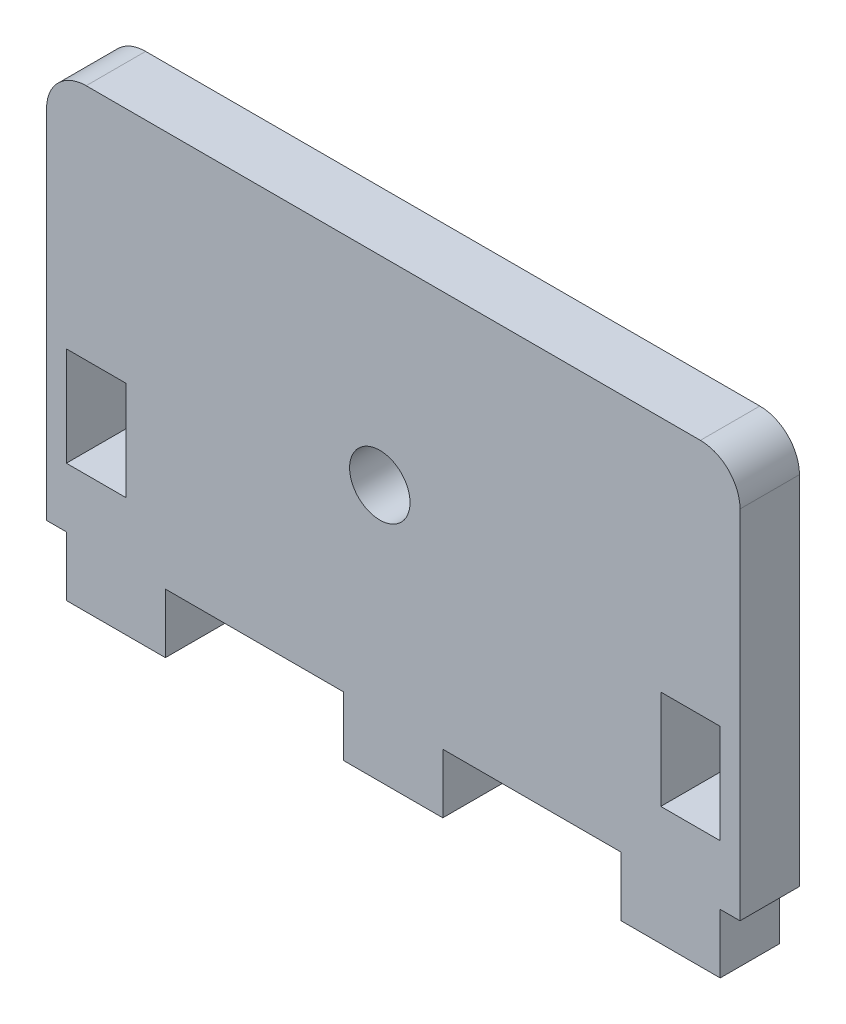
SolidWorks part; units mm, degrees
ref_plane "Front Plane" through (0, 0, 0) normal (0, 0, 1) x (1, 0, 0)
ref_plane "Top Plane" through (0, 0, 0) normal (0, 1, 0) x (1, 0, 0)
ref_plane "Right Plane" through (0, 0, 0) normal (1, 0, 0) x (0, 0, -1)
sketch "Sketch1" plane through (0, 0, 0) normal (0, 0, 1) x (1, 0, 0)
  line L0 (-11.5, -10) -> (-2.5, -10)
  line L1 (-17.5, 10) -> (17.5, 10)
  line L2 (-17.5, 10) -> (-17.5, -10)
  line L3 (-17.5, -10) -> (-16.5, -10)
  line L4 (17.5, 10) -> (17.5, -10)
  line L5 (-17.5, 10) -> (17.5, -10) construction
  line L6 (-17.5, -10) -> (17.5, 10) construction
  line L8 (-16.5, -10) -> (-16.5, -13)
  line L9 (-16.5, -13) -> (-11.5, -13)
  line L10 (-11.5, -10) -> (-11.5, -13)
  line L12 (-2.5, -10) -> (-2.5, -13)
  line L13 (-2.5, -13) -> (2.5, -13)
  line L14 (2.5, -10) -> (2.5, -13)
  line L16 (11.5, -10) -> (11.5, -13)
  line L17 (11.5, -13) -> (16.5, -13)
  line L18 (16.5, -10) -> (16.5, -13)
  line L19 (2.5, -10) -> (11.5, -10)
  line L20 (16.5, -10) -> (17.5, -10)
  point P0 (0, 0)
  point P18 (0, -13)
  dimension "D1" = 5
  dimension "D2" = 3
  dimension "D3" = 1
  dimension "D4" = 1
  dimension "D5" = 35
  dimension "D6" = 20
extrude "Boss-Extrude1" add sketch "Sketch1" along normal blind 3
fillet "Fillet1" radius 2 2 edges at (-17.5, 10, 1.5) (17.5, 10, 1.5)
sketch "Sketch4" plane through (0, 0, 3) normal (0, 0, 1) x (1, 0, 0)
  line L0 (-16.5, -13) -> (-11.5, -13) construction
  line L1 (17.5, -10) -> (17.5, 8) construction
  line L2 (-17.5, 8) -> (-17.5, -10) construction
  line L3 (-16.5, -2) -> (-13.5, -2)
  line L4 (-16.5, -2) -> (-16.5, -7)
  line L5 (-16.5, -7) -> (-13.5, -7)
  line L6 (-13.5, -2) -> (-13.5, -7)
  line L7 (13.5, -2) -> (16.5, -2)
  line L8 (13.5, -2) -> (13.5, -7)
  line L9 (13.5, -7) -> (16.5, -7)
  line L10 (16.5, -2) -> (16.5, -7)
  circle A0 centre (-0.68, -0.05) radius 1.525
  dimension "D1" = 3.05
  dimension "D2" = 12.95
  dimension "D3" = 18.18
  dimension "D4" = 1
  dimension "D5" = 1
  dimension "D6" = 3
  dimension "D7" = 5
  dimension "D8" = 6
extrude "Cut-Extrude1" cut sketch "Sketch4" against normal through all
